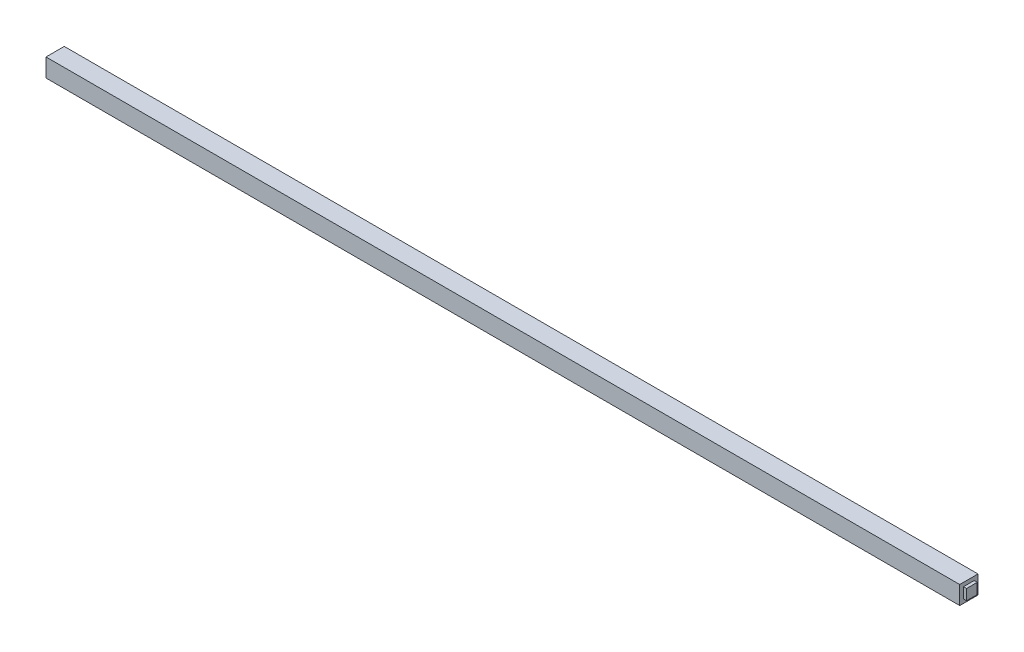
SolidWorks part; units mm, degrees
ref_plane "Front Plane" through (0, 0, 0) normal (0, 0, 1) x (1, 0, 0)
ref_plane "Top Plane" through (0, 0, 0) normal (0, 1, 0) x (1, 0, 0)
ref_plane "Right Plane" through (0, 0, 0) normal (1, 0, 0) x (0, 0, -1)
sketch "Sketch1" plane through (0, 0, 0) normal (0, 1, 0) x (1, 0, 0)
  line L1 (0, 0) -> (300, 0)
  line L2 (0, 0) -> (0, 6)
  line L3 (0, 6) -> (300, 6)
  line L4 (300, 0) -> (300, 6)
  dimension "D1" = 300
  dimension "D2" = 6
extrude "Boss-Extrude1" add sketch "Sketch1" along normal blind 6
sketch "Sketch2" plane through (0, 6, 0) normal (0, 1, 0) x (1, 0, 0)
  line L0 (150, 22.3479) -> (150, -6.1848)
  line L1 (0, 6) -> (0, 0) construction
  point P3 (150, 8.0816)
  dimension "D1" = 150
ref_plane "Plane1" through (150, 0, 0) normal (1, 0, 0) x (0, 0, -1)
sketch "Sketch3" plane through (300, 0, 0) normal (1, 0, 0) x (0, 0, -1)
  line L0 (0, 0) -> (6, 0) construction
  line L1 (1.25, 4.75) -> (4.75, 4.75)
  line L2 (1.25, 4.75) -> (1.25, 1.25)
  line L3 (1.25, 1.25) -> (4.75, 1.25)
  line L4 (4.75, 4.75) -> (4.75, 1.25)
  line L5 (1.25, 4.75) -> (4.75, 1.25) construction
  line L6 (1.25, 1.25) -> (4.75, 4.75) construction
  line L7 (6, 6) -> (6, 0) construction
  point P0 (3, 3)
  dimension "D1" = 3.5
  dimension "D2" = 3.5
  dimension "D3" = 3
  dimension "D4" = 3
extrude "Boss-Extrude2" add sketch "Sketch3" along normal blind 1
mirror "Mirror1" about plane through (150, 0, 0) normal (1, 0, 0) of "Boss-Extrude2"
